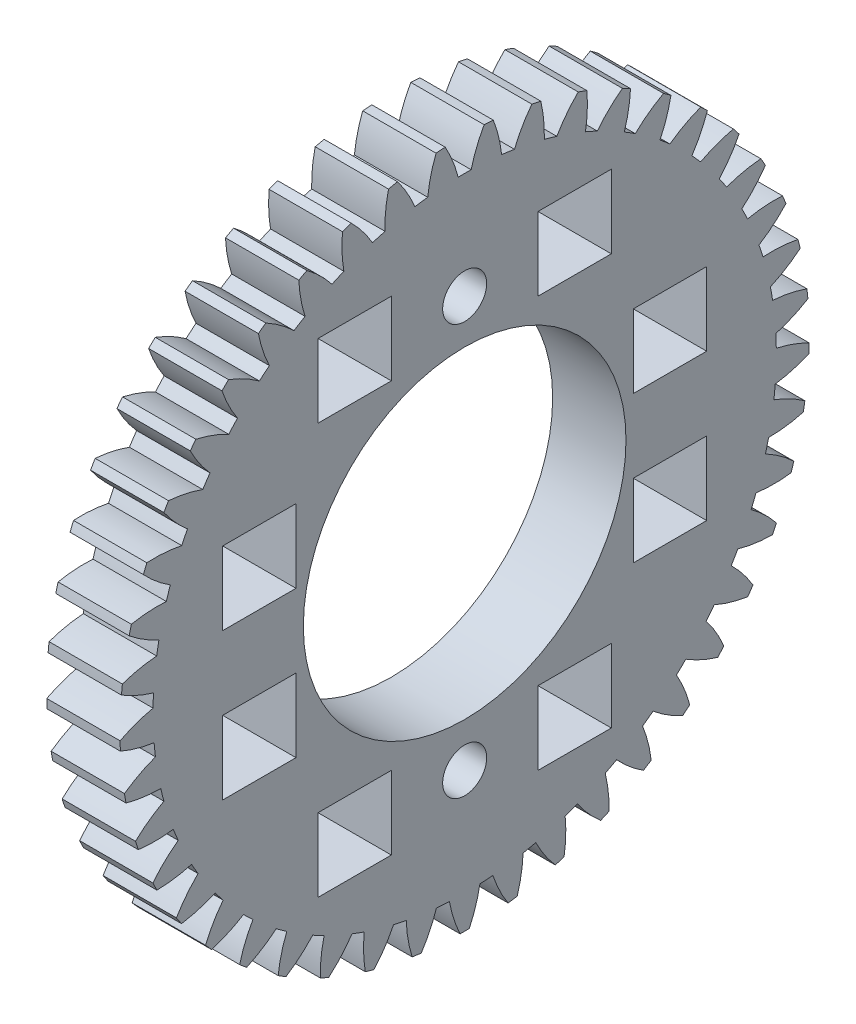
SolidWorks part; units mm, degrees
ref_plane "Plane1" through (0, 0, 0) normal (0, 0, 1) x (1, 0, 0)
ref_plane "Plane2" through (0, 0, 0) normal (0, 1, 0) x (1, 0, 0)
ref_plane "Plane3" through (0, 0, 0) normal (1, 0, 0) x (0, 0, -1)
sketch "HoldingSke" plane through (0, 0, 0) normal (0, 1, 0) x (1, 0, 0)
  line L0 (0, 0) -> (0.7071, -0.7071)
  line L1 (-15, 0) -> (100, 0) construction
  line L2 (0, 0) -> (-2.1039, 2.3779)
  line L3 (0, 0) -> (-11.863, 4.5341)
  line L4 (0, 0) -> (6.1066, 6.1066)
  line L5 (0, 0) -> (-46.8476, -17.4728)
  line L6 (0, 0) -> (-4.1448, -2.7965)
  line L7 (-2.1039, 2.3779) -> (8.6586, 51.2059)
  line L8 (-76.2, 54.61) -> (-74.4, 54.61)
  line L9 (-71.009, 38.7566) -> (-53.1078, 45.2721)
  line L10 (-76.2, 71.12) -> (104.1128, 71.12)
  line L11 (0, 0) -> (-5, 0)
  line L12 (-76.2, 101.6) -> (-76.162, 101.6)
  line L13 (24.9733, 27.94) -> (52.9518, 28.4284)
  line L14 (24.9733, 27.94) -> (24.9743, 27.94)
  line L15 (24.9733, 27.94) -> (100.4006, 29.5858)
  line L16 (-63.627, -1) -> (-12.827, -1)
  circle A0 centre (0, 0) radius 5
  circle A1 centre (0, 0) radius 21.249
  circle A2 centre (0, 0) radius 37.5
  circle A3 centre (0, 0) radius 5
  dimension "MHD" = 42.498
  dimension "Hub_dia" = 75
  dimension "Bore" = 10
  dimension "MBD" = 10
  dimension "Num_teeth" = 45
  dimension "Pitch" = 1
  dimension "Overall_len" = 50
  dimension "Show_teeth" = 45
  dimension "Thickness" = 5
  dimension "OAL" = 50.0001
  dimension "T_dim" = 1.8
  dimension "Ap" = 20
  dimension "H" = 19.05
  dimension "Pitch_radius" = 180.3128
  dimension "Width" = 5
  dimension "Backlash" = 0.038
  dimension "Addendum_fac" = 1
  dimension "Dedendum_fac" = 1.25
  dimension "Clearance_fac" = 0.25
  dimension "Dedendum_add" = 0.001
  dimension "Module" = 1
sketch "BasProSke" plane through (0, 0, 0) normal (0, 1, 0) x (1, 0, 0)
  line L0 (-10, 0) -> (60, 0) construction
  line L1 (0, 0) -> (0, 23.5)
  line L2 (0, 0) -> (5, 0)
  line L3 (5, 0) -> (5, 23.5)
  line L4 (5, 23.5) -> (0, 23.5)
  dimension "Thickness" = 5
  dimension "Diameter" = 47
revolve "Base-Revolve" add sketch "BasProSke" angle 360 about L0
sketch "TooCutSke" plane through (0, 0, 0) normal (1, 0, 0) x (0, 0, -1)
  line L1 (0, 0) -> (0, 107) construction
  line L2 (0, 0) -> (-0.8517, 22.4839) construction
  line L3 (0, 0) -> (-3.1374, 44.8675) construction
  line L4 (-0.8517, 22.4839) -> (-1.5687, 22.4337) construction
  arc A0 (0.4426, 21.2444) -> (-0.4426, 21.2444) centre (0, 0) ccw
  arc A1 (1.3407, 23.4872) -> (-1.3407, 23.4872) centre (0, 0) ccw
  circle A2 centre (0, 0) radius 22.5 construction
  circle A3 centre (0, 0) radius 21.1431 construction
  arc A4 (-0.4426, 21.2444) -> (-1.3407, 23.4872) centre (-9.1711, 19.0505) ccw
  arc A5 (1.3407, 23.4872) -> (0.4426, 21.2444) centre (9.1711, 19.0505) ccw
  dimension "Root_dia" = 42.498
  dimension "Overcut_dia" = 47.0508
  dimension "Pitch_dia" = 45
  dimension "Base_dia" = 42.2862
  dimension "Flank_rad" = 9
  dimension "Half_ang" = 4
  dimension "Half_CT" = 0.7187
extrude "ToothCut" cut sketch "TooCutSke" along normal through all
fillet "Breaks" [suppressed] radius 0.02
fillet "RootFillets" [suppressed] radius 0.251
pattern_circular "TeethCuts" count 45 every 8 about axis through (-10, 0, 0) along (1, 0, 0) of "ToothCut", "RootFillets", "Breaks"
sketch "HubNeaOneSke" plane through (0, 0, 0) normal (-1, 0, 0) x (0, 0, 1)
  circle A0 centre (0, 0) radius 21.249
  dimension "Diameter" = 42.498
extrude "HubNearOne" [suppressed] add sketch "HubNeaOneSke" along normal blind 45.0001
sketch "HubNeaBotSke" plane through (0, 0, 0) normal (-1, 0, 0) x (0, 0, 1)
  circle A0 centre (0, 0) radius 21.249
  dimension "Diameter" = 42.498
extrude "HubNearBoth" [suppressed] add sketch "HubNeaBotSke" along normal blind 22.5
ref_plane "FarPln" through (5, 0, 0) normal (1, 0, 0) x (0, 0, -1)
sketch "HubFarSke" plane through (5, 0, 0) normal (1, 0, 0) x (0, 0, -1)
  circle A0 centre (0, 0) radius 21.249
  dimension "Diameter" = 42.498
extrude "HubFar" [suppressed] add sketch "HubFarSke" along normal blind 22.5
sketch "BorSke" plane through (0, 0, 0) normal (1, 0, 0) x (0, 0, -1)
  circle A0 centre (0, 0) radius 5
  dimension "Diameter" = 10
extrude "Bore" cut sketch "BorSke" along normal mid plane 100.0001
sketch "KeySke" plane through (0, 0, 0) normal (1, 0, 0) x (0, 0, -1)
  line L0 (-2, 0) -> (-2, 6.8)
  line L1 (-2, 6.8) -> (2, 6.8)
  line L2 (2, 6.8) -> (2, 0)
  line L3 (0, 0) -> (0, 34) construction
  line L4 (-2, 0) -> (2, 0)
  dimension "Offset" = 6.8
  dimension "Width" = 4
extrude "Keyway" [suppressed] cut sketch "KeySke" along normal mid plane 100.0001
pattern_circular "Keyway2" [suppressed] count 2 every 90 about axis through (-10, 0, 0) along (1, 0, 0)
sketch "Sketch1" plane through (5, 0, 0) normal (1, 0, 0) x (0, 0, -1)
  line L0 (-7.5, 14) -> (7.5, 14) construction
  line L1 (-10, 16.5) -> (-5, 16.5)
  line L2 (-10, 16.5) -> (-10, 11.5)
  line L3 (-10, 11.5) -> (-5, 11.5)
  line L4 (-5, 16.5) -> (-5, 11.5)
  line L5 (-10, 16.5) -> (-5, 11.5) construction
  line L6 (-10, 11.5) -> (-5, 16.5) construction
  line L7 (5, 16.5) -> (10, 16.5)
  line L8 (5, 16.5) -> (5, 11.5)
  line L9 (5, 11.5) -> (10, 11.5)
  line L10 (10, 16.5) -> (10, 11.5)
  line L11 (5, 16.5) -> (10, 11.5) construction
  line L12 (5, 11.5) -> (10, 16.5) construction
  line L13 (0, 0) -> (0, 19.4066) construction
  line L14 (-7.5, -14) -> (7.5, -14) construction
  line L15 (-10, -11.5) -> (-5, -11.5)
  line L16 (-10, -11.5) -> (-10, -16.5)
  line L17 (-10, -16.5) -> (-5, -16.5)
  line L18 (-5, -11.5) -> (-5, -16.5)
  line L19 (-10, -11.5) -> (-5, -16.5) construction
  line L20 (-10, -16.5) -> (-5, -11.5) construction
  line L21 (5, -11.5) -> (10, -11.5)
  line L22 (5, -11.5) -> (5, -16.5)
  line L23 (5, -16.5) -> (10, -16.5)
  line L24 (10, -11.5) -> (10, -16.5)
  line L25 (5, -11.5) -> (10, -16.5) construction
  line L26 (5, -16.5) -> (10, -11.5) construction
  line L27 (-16.5, -2.5) -> (-11.5, -2.5)
  line L28 (-16.5, 7.5) -> (-11.5, 7.5)
  line L29 (-16.5, 7.5) -> (-16.5, 2.5)
  line L30 (-16.5, 2.5) -> (-11.5, 2.5)
  line L31 (-11.5, 7.5) -> (-11.5, 2.5)
  line L32 (-16.5, 7.5) -> (-11.5, 2.5) construction
  line L33 (-16.5, 2.5) -> (-11.5, 7.5) construction
  line L34 (-16.5, -2.5) -> (-16.5, -7.5)
  line L35 (-16.5, -7.5) -> (-11.5, -7.5)
  line L36 (-11.5, -2.5) -> (-11.5, -7.5)
  line L37 (-16.5, -2.5) -> (-11.5, -7.5) construction
  line L38 (-16.5, -7.5) -> (-11.5, -2.5) construction
  line L39 (-14, -5) -> (-14, 5) construction
  line L40 (11.5, -2.5) -> (16.5, -2.5)
  line L41 (11.5, 7.5) -> (16.5, 7.5)
  line L42 (11.5, 7.5) -> (11.5, 2.5)
  line L43 (11.5, 2.5) -> (16.5, 2.5)
  line L44 (16.5, 7.5) -> (16.5, 2.5)
  line L45 (11.5, 7.5) -> (16.5, 2.5) construction
  line L46 (11.5, 2.5) -> (16.5, 7.5) construction
  line L47 (11.5, -2.5) -> (11.5, -7.5)
  line L48 (11.5, -7.5) -> (16.5, -7.5)
  line L49 (16.5, -2.5) -> (16.5, -7.5)
  line L50 (11.5, -2.5) -> (16.5, -7.5) construction
  line L51 (11.5, -7.5) -> (16.5, -2.5) construction
  line L52 (14, -5) -> (14, 5) construction
  line L53 (0, 0) -> (26.9952, 0) construction
  circle A0 centre (0, 14) radius 1.5
  circle A1 centre (0, -14) radius 1.5
  circle A2 centre (0, 0) radius 14 construction
  circle A3 centre (0, 0) radius 11
  point P0 (-7.5, 14)
  point P5 (7.5, 14)
  point P17 (14, -5)
  point P18 (-7.5, -14)
  point P23 (7.5, -14)
  point P32 (-14, -5)
  point P33 (-14, 5)
  point P44 (14, 5)
  point P58 (14, 0)
  point P59 (-14, 0)
  dimension "D4" = 5
  dimension "D7" = 28
  dimension "D8" = 3
  dimension "D1" = 5
  dimension "D2" = 5
  dimension "D3" = 10
  dimension "D5" = 5
  dimension "D6" = 5
extrude "Cut-Extrude1" cut sketch "Sketch1" against normal blind 10
equation "' \"Module@HoldingSke\" = 6.35"
equation "' \"Num_teeth@HoldingSke\" = 12"
equation "' \"Ap@HoldingSke\" =  20"
equation "' \"Ap@HoldingSke\" = 20"
equation "' \"Width@HoldingSke\" = 0.5 * 25.4"
equation "' \"Hub_dia@HoldingSke\"= 1 * 25.4"
equation "' \"Hub_dia@HoldingSke\" = 1 * 25.4"
equation "' \"Overall_len@HoldingSke\" = 1.0 * 25.4"
equation "' \"Bore@HoldingSke\" = 0.75 * 25.4"
equation "' \"T_dim@HoldingSke\" = 0.1 * 25.4"
equation "' \"Width@KeySke\" = 0.25 * 25.4"
equation "' \"Show_teeth@HoldingSke\" = 13"
equation "' \"Backlash@HoldingSke\" = 0.009 * 25.4"
equation "' \"Addendum_fac@HoldingSke\" = 1.0"
equation "' \"Dedendum_fac@HoldingSke\" = 1.25"
equation "' \"Dedendum_add@HoldingSke\" = 0.00005 * 25.4"
equation "' \"Clearance_fac@HoldingSke\" = 0.25"
equation "\"Pitch@HoldingSke\" = 1 / \"Module@HoldingSke\""
equation "\"Overcut_dia@TooCutSke\" = (\"Num_teeth@HoldingSke\" + 2 * \"Addendum_fac@HoldingSke\") / \"Pitch@HoldingSke\" + 0.002 * 25.4"
equation "\"Pitch_dia@TooCutSke\" = \"Num_teeth@HoldingSke\" / \"Pitch@HoldingSke\""
equation "\"Base_dia@TooCutSke\" = \"Num_teeth@HoldingSke\" / \"Pitch@HoldingSke\" * cos((\"Ap@HoldingSke\"  * 3.14159265 / 180))"
equation "\"Root_dia@TooCutSke\" = (\"Num_teeth@HoldingSke\" + 2) / \"Pitch@HoldingSke\" - 2 * (\"Addendum_fac@HoldingSke\" + \"Dedendum_fac@HoldingSke\") / \"Pitch@HoldingSke\" - \"Dedendum_add@HoldingSke\" * 2"
equation "\"Half_ang@TooCutSke\" = 180 / \"Num_teeth@HoldingSke\""
equation "\"Half_CT@TooCutSke\" = \"Num_teeth@HoldingSke\" / \"Pitch@HoldingSke\" * sin((3.14159265 / 2 / \"Num_teeth@HoldingSke\")) / 2 - 7 * \"Backlash@HoldingSke\" / 4"
equation "\"Flank_rad@TooCutSke\" = \"Num_teeth@HoldingSke\" / \"Pitch@HoldingSke\" / 5"
equation "\"Radius@RootFillets\" = \"Clearance_fac@HoldingSke\" / \"Pitch@HoldingSke\" + \"Dedendum_add@HoldingSke\""
equation "\"Break_rad@Breaks\" = 0.02 / \"Pitch@HoldingSke\""
equation "\"Thickness@HoldingSke\" = \"Width@HoldingSke\""
equation "\"OAL@HoldingSke\" = \"Thickness@HoldingSke\""
equation "\"MHD@HoldingSke\" = (\"Num_teeth@HoldingSke\" + 2) / \"Pitch@HoldingSke\" - 2 * (\"Addendum_fac@HoldingSke\" + \"Dedendum_fac@HoldingSke\")  / \"Pitch@HoldingSke\" - \"Dedendum_add@HoldingSke\" * 2"
equation "\"MBD@HoldingSke\" = (\"Num_teeth@HoldingSke\" + 2) / \"Pitch@HoldingSke\" - 2 * (\"Addendum_fac@HoldingSke\" + \"Dedendum_fac@HoldingSke\")  / \"Pitch@HoldingSke\" - \"Dedendum_add@HoldingSke\" * 2 - 0.002 * 25.4"
equation "\"MHD@HoldingSke\" = ((sgn( \"MHD@HoldingSke\" - \"Hub_dia@HoldingSke\" )-1)*( \"MHD@HoldingSke\" - \"Hub_dia@HoldingSke\" ))/-2+ \"Hub_dia@HoldingSke\""
equation "\"MBD@HoldingSke\" = ((sgn( \"MBD@HoldingSke\" - \"Bore@HoldingSke\" )-1)*( \"MBD@HoldingSke\" - \"Bore@HoldingSke\" ))/-2+ \"Bore@HoldingSke\""
equation "\"OAL@HoldingSke\" = ((sgn( \"OAL@HoldingSke\" - \"Overall_len@HoldingSke\" )+1)*( \"OAL@HoldingSke\" - \"Overall_len@HoldingSke\" ))/2 + \"Overall_len@HoldingSke\" + 0.000002 * 25.4"
equation "\"Num_teeth@TeethCuts\" = int( \"Show_teeth@HoldingSke\" ) + 1"
equation "\"Num_teeth@TeethCuts\" = ((sgn( \"Num_teeth@TeethCuts\" - \"Num_teeth@HoldingSke\" )-1)*( \"Num_teeth@TeethCuts\" - \"Num_teeth@HoldingSke\" ))/-2+ \"Num_teeth@HoldingSke\""
equation "\"Num_teeth@TeethCuts\" = ((sgn( \"Num_teeth@TeethCuts\" - 2.0)+1)*( \"Num_teeth@TeethCuts\" - 2.0))/2 +2.0"
equation "\"Angle@TeethCuts\" = 360.0 / \"Num_teeth@HoldingSke\""
equation "\"Diameter@BasProSke\" = (\"Num_teeth@HoldingSke\" + 2 * \"Addendum_fac@HoldingSke\") / \"Pitch@HoldingSke\""
equation "\"Thickness@BasProSke\"  = \"Thickness@HoldingSke\""
equation "' \"Fillet_rad@BasProSke\" =  \"Thickness@HoldingSke\" * 0.05"
equation "' \"Fillet_rad@BasProSke\" = \"Thickness@HoldingSke\" * 0.05"
equation "\"MHD@HoldingSke\" = ((sgn( \"MHD@HoldingSke\" - \"Root_dia@TooCutSke\" )-1)*( \"MHD@HoldingSke\" - \"Root_dia@TooCutSke\" ))/-2+ \"Root_dia@TooCutSke\""
equation "\"Diameter@HubNeaOneSke\" = \"MHD@HoldingSke\""
equation "\"Length@HubNearOne\" = \"OAL@HoldingSke\" - \"Thickness@BasProSke\""
equation "\"Diameter@HubNeaBotSke\" = \"MHD@HoldingSke\""
equation "\"Length@HubNearBoth\" = ( \"OAL@HoldingSke\" - \"Thickness@BasProSke\" ) / 2.0"
equation "\"Thickness@FarPln\" = \"Thickness@BasProSke\""
equation "\"Diameter@HubFarSke\" = \"MHD@HoldingSke\""
equation "\"Length@HubFar\" = ( \"OAL@HoldingSke\" - \"Thickness@BasProSke\" ) / 2.0"
equation "\"Diameter@BorSke\" = \"MBD@HoldingSke\""
equation "\"D1@Bore\" = \"OAL@HoldingSke\" * 2.0"
equation "\"D1@Keyway\" = \"OAL@HoldingSke\" * 2.0"
equation "\"Offset@KeySke\" = \"T_dim@HoldingSke\" + \"MBD@HoldingSke\" / 2.0"
